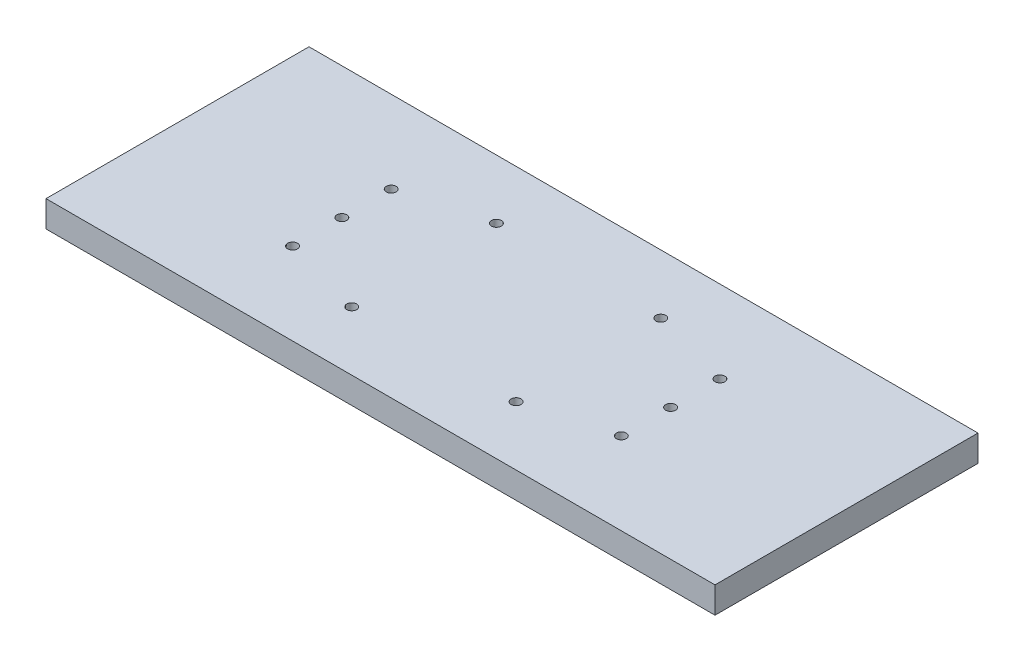
SolidWorks part; units mm, degrees
ref_plane "Front Plane" through (0, 0, 0) normal (0, 0, 1) x (1, 0, 0)
ref_plane "Top Plane" through (0, 0, 0) normal (0, 1, 0) x (1, 0, 0)
ref_plane "Right Plane" through (0, 0, 0) normal (1, 0, 0) x (0, 0, -1)
sketch "Sketch1" plane through (0, 0, 0) normal (0, 1, 0) x (1, 0, 0)
  line L1 (-203.5, 80) -> (203.5, 80)
  line L2 (-203.5, 80) -> (-203.5, -80)
  line L3 (-203.5, -80) -> (203.5, -80)
  line L4 (203.5, 80) -> (203.5, -80)
  line L5 (-203.5, 80) -> (203.5, -80) construction
  line L6 (-203.5, -80) -> (203.5, 80) construction
  point P0 (0, 0)
  dimension "D1" = 407
  dimension "D2" = 160
extrude "Boss-Extrude1" add sketch "Sketch1" along normal blind 16
sketch "Sketch2" plane through (0, 16, 0) normal (0, 1, 0) x (1, 0, 0)
  line L0 (-203.5, 80) -> (-203.5, -80) construction
  line L1 (-203.5, 0) -> (203.5, 0) construction
  line L2 (203.5, -80) -> (203.5, 80) construction
  line L3 (-3.5, 108.8336) -> (-3.5, -98.4323) construction
  circle A0 centre (-53.5, 44) radius 3
  circle A1 centre (46.5, 44) radius 3
  circle A2 centre (46.5, -44) radius 3
  circle A3 centre (-53.5, -44) radius 3
  circle A4 centre (96.5, 0) radius 3
  circle A5 centre (96.5, 30) radius 3
  circle A6 centre (96.5, -30) radius 3
  circle A7 centre (-103.5, 30) radius 3
  circle A8 centre (-103.5, 0) radius 3
  circle A9 centre (-103.5, -30) radius 3
  dimension "D1" = 150
  dimension "D3" = 100
  dimension "D5" = 6
  dimension "D2" = 44
  dimension "D4" = 50
  dimension "D6" = 100
  dimension "D7" = 30
extrude "Cut-Extrude1" cut sketch "Sketch2" against normal through all
